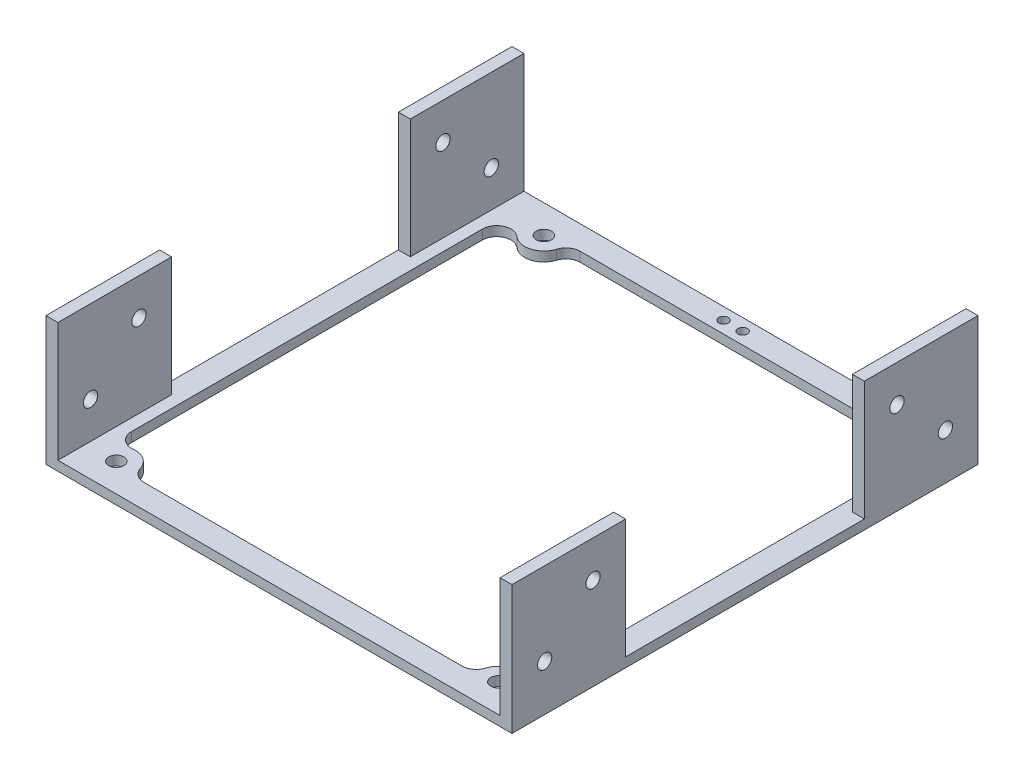
SolidWorks part; units mm, degrees
ref_plane "Front" through (0, 0, 0) normal (0, 0, 1) x (1, 0, 0)
ref_plane "Top" through (0, 0, 0) normal (0, 1, 0) x (1, 0, 0)
ref_plane "Right" through (0, 0, 0) normal (1, 0, 0) x (0, 0, -1)
sketch "Эскиз1" plane through (0, 0, 0) normal (0, 1, 0) x (1, 0, 0)
  line L0 (0, 0) -> (97.6, 97.6) construction
  line L1 (0, 0) -> (97.6, 0)
  line L2 (0, 0) -> (0, 97.6)
  line L3 (0, 97.6) -> (97.6, 97.6)
  line L4 (97.6, 0) -> (97.6, 97.6)
  line L5 (97.6, 0) -> (0, 97.6) construction
  line L25 (79.5765, 92.6) -> (19.2935, 92.6)
  line L27 (92.6, 85.5105) -> (92.6, 12.8897)
  line L29 (5, 86.393) -> (5, 12.8897)
  line L33 (82.1165, 5) -> (15.4835, 5)
  circle A0 centre (86.265, 91.665) radius 1.59
  circle A1 centre (88.805, 5.935) radius 1.59
  circle A2 centre (8.795, 5.935) radius 1.59
  circle A3 centre (12.605, 91.665) radius 1.59
  arc A29 (9.9736, 88.6524) -> (16.427, 90.485) centre (12.605, 91.665) ccw
  arc A30 (82.443, 90.485) -> (88.1707, 88.1481) centre (86.265, 91.665) ccw
  arc A31 (89.2593, 9.9091) -> (84.983, 7.115) centre (88.805, 5.935) ccw
  arc A32 (12.617, 7.115) -> (8.3407, 9.9091) centre (8.795, 5.935) ccw
  arc A33 (92.6, 12.8897) -> (89.2593, 9.9091) centre (89.6, 12.8897) cw
  arc A34 (82.1165, 5) -> (84.983, 7.115) centre (82.1165, 8) ccw
  arc A35 (15.4835, 5) -> (12.617, 7.115) centre (15.4835, 8) cw
  arc A36 (5, 12.8897) -> (8.3407, 9.9091) centre (8, 12.8897) ccw
  arc A37 (9.9736, 88.6524) -> (5, 86.393) centre (8, 86.393) ccw
  arc A38 (88.1707, 88.1481) -> (92.6, 85.5105) centre (89.6, 85.5105) cw
  arc A39 (19.2935, 92.6) -> (16.427, 90.485) centre (19.2935, 89.6) ccw
  arc A40 (82.443, 90.485) -> (79.5765, 92.6) centre (79.5765, 89.6) ccw
  point P19 (48.8, 48.8)
  dimension "D1" = 3
  dimension "D2" = 3
  dimension "D3" = 3
  dimension "D4" = 3
  dimension "D5" = 3
  dimension "D6" = 3
extrude "Бобышка-Вытянуть1" add sketch "Эскиз1" along normal blind 2
sketch "Эскиз2" plane through (0, 2, 0) normal (0, 1, 0) x (1, 0, 0)
  line L0 (48.8, 97.6) -> (48.8, 92.6) construction
  line L1 (97.6, 97.6) -> (0, 97.6) construction
  line L2 (79.5765, 92.6) -> (19.2935, 92.6) construction
  circle A2 centre (46.8, 95.1) radius 1
  circle A3 centre (50.8, 95.1) radius 1
extrude "Вырез-Вытянуть1" cut sketch "Эскиз2" against normal through all
sketch "Эскиз7" plane through (0, 2, 0) normal (0, 1, 0) x (1, 0, 0)
  line L0 (3.715, 37.25) -> (3.715, 2.855) construction
  line L1 (5.7156, 0.8544) -> (37.2506, 0.8544) construction
  line L2 (39.6506, 3.2544) -> (57.9506, 3.2544) construction
  line L3 (60.3506, 0.8544) -> (91.8856, 0.8544) construction
  line L4 (93.885, 2.8538) -> (93.885, 37.25) construction
  line L5 (91.485, 39.65) -> (91.485, 57.95) construction
  line L6 (93.885, 60.35) -> (93.885, 94.745) construction
  line L7 (91.885, 96.745) -> (60.35, 96.745) construction
  line L8 (57.95, 94.345) -> (39.65, 94.345) construction
  line L9 (37.25, 96.745) -> (5.715, 96.745) construction
  line L10 (3.715, 94.745) -> (3.715, 60.35) construction
  line L11 (6.115, 57.95) -> (6.115, 39.65) construction
  line L12 (6.115, 48.8) -> (91.485, 48.8) construction
  line L13 (48.8006, 3.2544) -> (48.8, 94.345) construction
  line L15 (0, 0) -> (2.5, 0)
  line L16 (0, 0) -> (0, 23.8)
  line L17 (0, 23.8) -> (2.5, 23.8)
  line L18 (2.5, 0) -> (2.5, 23.8)
  line L27 (0, 97.6) -> (2.5, 97.6)
  line L28 (0, 97.6) -> (0, 73.8)
  line L29 (0, 73.8) -> (2.5, 73.8)
  line L30 (2.5, 97.6) -> (2.5, 73.8)
  line L32 (97.6, 97.6) -> (95.1, 97.6)
  line L33 (97.6, 97.6) -> (97.6, 73.8)
  line L34 (97.6, 73.8) -> (95.1, 73.8)
  line L35 (95.1, 97.6) -> (95.1, 73.8)
  line L36 (97.6, 0) -> (95.1, 0)
  line L37 (97.6, 0) -> (97.6, 23.8)
  line L38 (97.6, 23.8) -> (95.1, 23.8)
  line L39 (95.1, 0) -> (95.1, 23.8)
  arc A4 (3.715, 94.745) -> (5.715, 96.745) centre (5.715, 94.745) cw construction
  arc A5 (38.45, 95.545) -> (37.25, 96.745) centre (37.25, 95.545) ccw construction
  arc A6 (38.45, 95.545) -> (39.65, 94.345) centre (39.65, 95.545) ccw construction
  arc A7 (59.15, 95.545) -> (57.95, 94.345) centre (57.95, 95.545) cw construction
  arc A8 (59.15, 95.545) -> (60.35, 96.745) centre (60.35, 95.545) cw construction
  arc A9 (59.1506, 2.0544) -> (60.3506, 0.8544) centre (60.3506, 2.0544) ccw construction
  arc A10 (59.1506, 2.0544) -> (57.9506, 3.2544) centre (57.9506, 2.0544) ccw construction
  arc A11 (38.4506, 2.0544) -> (39.6506, 3.2544) centre (39.6506, 2.0544) cw construction
  arc A12 (38.4506, 2.0544) -> (37.2506, 0.8544) centre (37.2506, 2.0544) cw construction
  arc A13 (3.715, 60.35) -> (4.915, 59.15) centre (4.915, 60.35) ccw construction
  arc A14 (6.115, 57.95) -> (4.915, 59.15) centre (4.915, 57.95) ccw construction
  arc A15 (6.115, 39.65) -> (4.915, 38.45) centre (4.915, 39.65) cw construction
  arc A16 (3.715, 37.25) -> (4.915, 38.45) centre (4.915, 37.25) cw construction
  arc A17 (93.885, 37.25) -> (92.685, 38.45) centre (92.685, 37.25) ccw construction
  arc A18 (91.485, 39.65) -> (92.685, 38.45) centre (92.685, 39.65) ccw construction
  arc A19 (91.485, 57.95) -> (92.685, 59.15) centre (92.685, 57.95) cw construction
  arc A20 (93.885, 60.35) -> (92.685, 59.15) centre (92.685, 60.35) cw construction
  arc A21 (91.885, 96.745) -> (93.885, 94.745) centre (91.885, 94.745) cw construction
  arc A22 (3.715, 2.855) -> (5.7156, 0.8544) centre (5.7156, 2.855) ccw construction
  arc A23 (91.8856, 0.8544) -> (93.885, 2.8538) centre (91.8856, 2.8538) ccw construction
extrude "Бобышка-Вытянуть2" add sketch "Эскиз7" along normal blind 25
sketch "Эскиз8" plane through (0, 0, 0) normal (-1, 0, 0) x (0, 0, 1)
  line L0 (-73.8, 2) -> (-97.6, 2) construction
  line L1 (-48.8, 2) -> (-48.8, 27) construction
  line L2 (-73.8, 2) -> (-23.8, 2) construction
  line L3 (-73.8, 2) -> (-97.6, 27) construction
  line L4 (-85.7, 14.5) -> (-80.6301, 19.3266) construction
  circle A0 centre (-80.6301, 19.3266) radius 1.5
  circle A1 centre (-90.7699, 9.6734) radius 1.5
  circle A2 centre (-6.8301, 9.6734) radius 1.5
  circle A3 centre (-16.9699, 19.3266) radius 1.5
extrude "Вырез-Вытянуть2" cut sketch "Эскиз8" against normal through all
